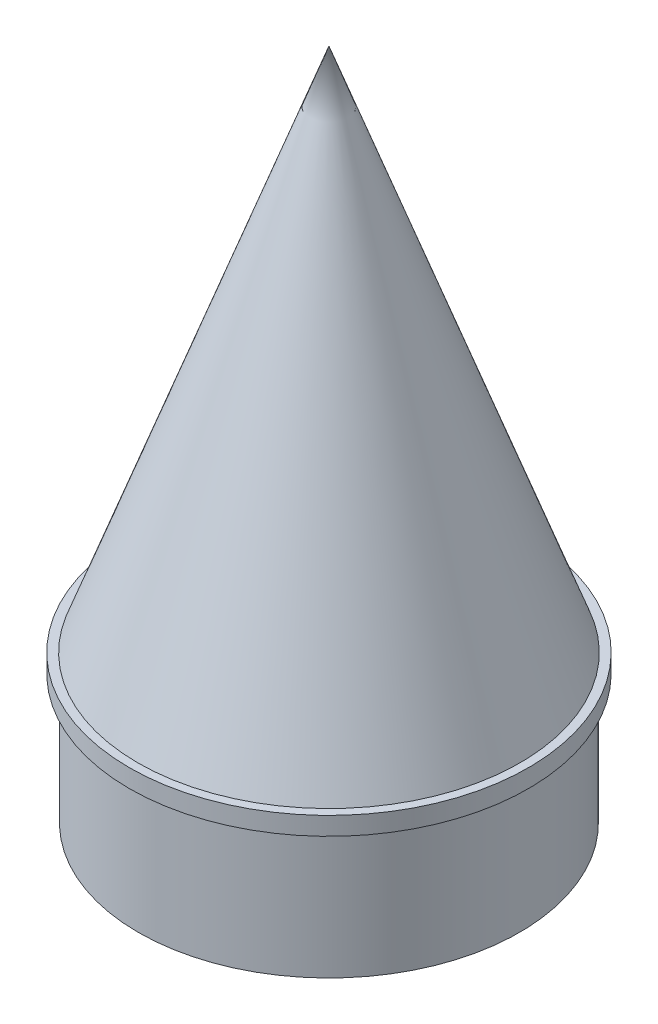
SolidWorks part; units mm, degrees
ref_plane "Front Plane" through (0, 0, 0) normal (0, 0, 1) x (1, 0, 0)
ref_plane "Top Plane" through (0, 0, 0) normal (0, 1, 0) x (1, 0, 0)
ref_plane "Right Plane" through (0, 0, 0) normal (1, 0, 0) x (0, 0, -1)
sketch "Sketch1" plane through (0, 0, 0) normal (0, 0, 1) x (1, 0, 0)
  line L0 (0, 0) -> (0, 65.3751) construction
  line L1 (0, 0) -> (-22.225, 0)
  line L2 (-22.225, 0) -> (-22.225, 2.1082)
  line L3 (0, 60.1272) -> (-20.0647, 5)
  line L4 (-20.0647, 5) -> (0, 5)
  line L5 (0, 5) -> (0, 0)
  line L6 (-22.225, 2.1082) -> (0, 63.1709)
  line L7 (0, 63.1709) -> (0, 60.1272)
  dimension "D1" = 290
  dimension "D2" = 1.041
  dimension "D3" = 5
  dimension "D6" = 44.45
revolve "Revolve1" add sketch "Sketch1" angle 360 mid plane about L0
ref_plane "Plane2" through (0, 4.5, 0) normal (0, -1, 0) x (-1, 0, 0)
sketch "Sketch9" plane through (0, 0, 0) normal (0, 0, 1) x (1, 0, 0)
  line L0 (-22.1611, 0) -> (-22.1611, -15)
  line L1 (-22.225, 0) -> (22.225, 0) construction
  line L2 (-22.1611, -15) -> (-21.1201, -15)
  line L3 (-21.1201, -15) -> (-21.1201, 2.1082)
  line L4 (22.225, 2.1082) -> (-22.225, 2.1082) construction
  line L6 (-22.1611, 0) -> (-23.2021, 0)
  line L7 (-23.2021, 0) -> (-23.2021, 2.1082)
  line L8 (-23.2021, 2.1082) -> (-21.1201, 2.1082)
  line L9 (0, 63.5368) -> (0, -15) construction
  dimension "D1" = 1.041
  dimension "D2" = 21.1201
  dimension "D3" = 15
  dimension "D4" = 1.041
revolve "Revolve3" add sketch "Sketch9" angle 360 about L9
sketch "Sketch10" plane through (0, 0, 0) normal (0, -1, 0) x (1, 0, 0)
  line L0 (-5.25, 13.25) -> (5.25, 13.25)
  line L1 (5.25, 13.25) -> (5.25, 10.25)
  line L2 (5.25, 10.25) -> (16.25, 10.25)
  line L3 (16.25, 10.25) -> (16.25, -10.25)
  line L4 (16.25, -10.25) -> (5.25, -10.25)
  line L5 (5.25, -10.25) -> (5.25, -13.25)
  line L6 (5.25, -13.25) -> (-5.25, -13.25)
  line L7 (-5.25, -13.25) -> (-5.25, -10.25)
  line L8 (-5.25, -10.25) -> (-16.25, -10.25)
  line L9 (-16.25, -10.25) -> (-16.25, 10.25)
  line L10 (-16.25, 10.25) -> (-5.25, 10.25)
  line L11 (-5.25, 10.25) -> (-5.25, 13.25)
  line L12 (0, 23.2021) -> (0, -23.2021) construction
  line L13 (-23.2021, 0) -> (23.2021, 0) construction
  circle A0 centre (0, 0) radius 23.2021 construction
  point P19 (0, 13.25)
  point P20 (16.25, 0)
  dimension "D1" = 3
  dimension "D2" = 20.5
  dimension "D3" = 32.5
  dimension "D4" = 10.5
extrude "Cut-Extrude1" cut sketch "Sketch10" against normal blind 3
